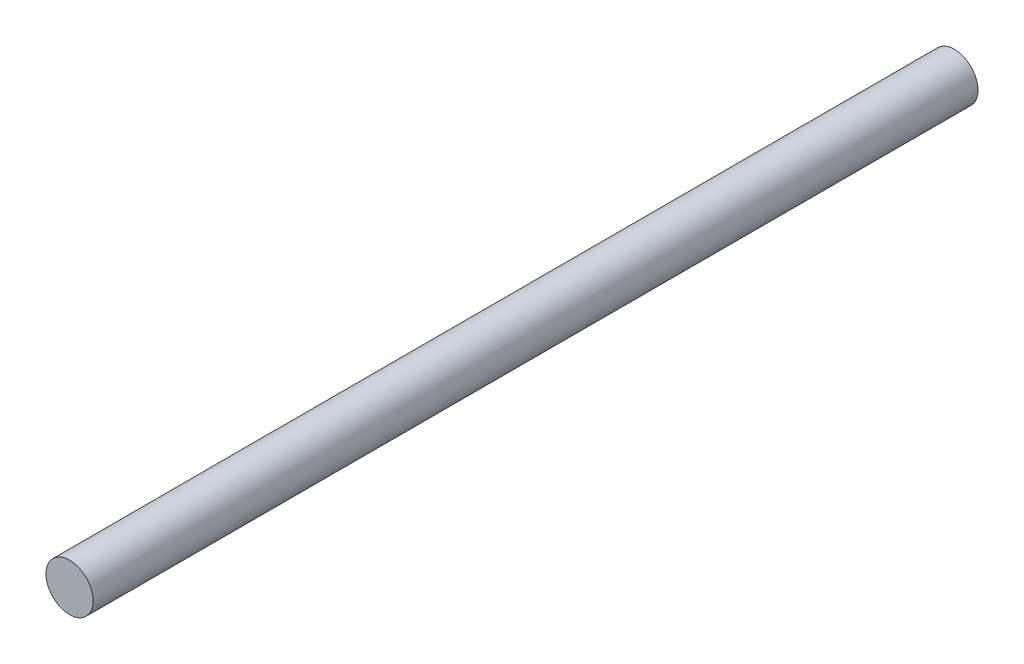
SolidWorks part; units mm, degrees
ref_plane "Plan de face" through (0, 0, 0) normal (0, 0, 1) x (1, 0, 0)
ref_plane "Plan de dessus" through (0, 0, 0) normal (0, 1, 0) x (1, 0, 0)
ref_plane "Plan de droite" through (0, 0, 0) normal (1, 0, 0) x (0, 0, -1)
sketch "Esquisse1" plane through (0, 0, 0) normal (0, 0, 1) x (1, 0, 0)
  circle A0 centre (0, 0) radius 4
  dimension "D1" = 8
extrude "Boss.-Extru.1" add sketch "Esquisse1" along normal blind 150
